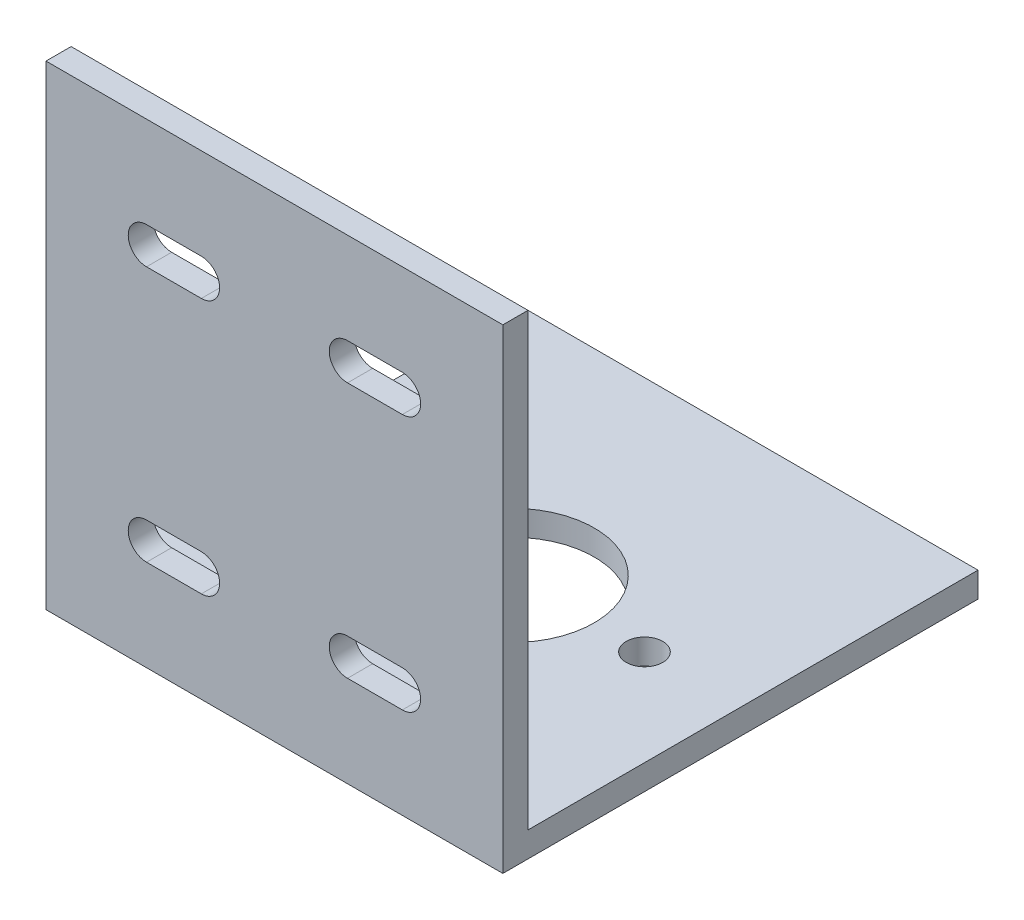
SolidWorks part; units mm, degrees
ref_plane "Front Plane" through (0, 0, 0) normal (0, 0, 1) x (1, 0, 0)
ref_plane "Top Plane" through (0, 0, 0) normal (0, 1, 0) x (1, 0, 0)
ref_plane "Right Plane" through (0, 0, 0) normal (1, 0, 0) x (0, 0, -1)
sketch "Sketch1" plane through (0, 0, 0) normal (0, 1, 0) x (1, 0, 0)
  line L1 (-25, -26) -> (25, -26)
  line L2 (-25, -26) -> (-25, 26)
  line L3 (-25, 26) -> (25, 26)
  line L4 (25, -26) -> (25, 26)
  circle A0 centre (0, 0) radius 9
  circle A1 centre (-14.5, 0) radius 2
  circle A2 centre (14.5, 0) radius 2
  point P11 (0, 0)
  dimension "D5" = 18
  dimension "D6" = 4
  dimension "D8" = 4
  dimension "D1" = 52
  dimension "D2" = 26
  dimension "D3" = 50
  dimension "D4" = 25
  dimension "D7" = 14.5
  dimension "D9" = 14.5
extrude "Boss-Extrude1" add sketch "Sketch1" along normal blind 2.75
sketch "Sketch2" plane through (0, 0, 0) normal (0, 1, 0) x (1, 0, 0)
  line L0 (25, -26) -> (25, 26) construction
  line L1 (-25, -26) -> (25, -26)
  line L2 (-25, -26) -> (-25, -23.25)
  line L3 (-25, -23.25) -> (25, -23.25)
  line L4 (25, -26) -> (25, -23.25)
  dimension "D1" = 2.75
extrude "Boss-Extrude2" add sketch "Sketch2" along normal blind 52
sketch "Sketch4" plane through (0, 0, 26) normal (0, 0, 1) x (1, 0, 0)
  line L0 (-14, 12) -> (-8, 12) construction
  line L1 (-14, 14) -> (-8, 14)
  line L2 (-14, 10) -> (-8, 10)
  line L3 (8, 12) -> (14, 12) construction
  line L4 (8, 14) -> (14, 14)
  line L5 (8, 10) -> (14, 10)
  line L6 (8, 40) -> (14, 40) construction
  line L7 (8, 42) -> (14, 42)
  line L8 (8, 38) -> (14, 38)
  line L9 (-14, 40) -> (-8, 40) construction
  line L10 (-14, 42) -> (-8, 42)
  line L11 (-14, 38) -> (-8, 38)
  line L12 (-14, 12) -> (8, 12) construction
  arc A0 (-14, 14) -> (-14, 10) centre (-14, 12) ccw
  arc A1 (-8, 10) -> (-8, 14) centre (-8, 12) ccw
  arc A2 (8, 14) -> (8, 10) centre (8, 12) ccw
  arc A3 (14, 10) -> (14, 14) centre (14, 12) ccw
  arc A4 (8, 42) -> (8, 38) centre (8, 40) ccw
  arc A5 (14, 38) -> (14, 42) centre (14, 40) ccw
  arc A6 (-14, 42) -> (-14, 38) centre (-14, 40) ccw
  arc A7 (-8, 38) -> (-8, 42) centre (-8, 40) ccw
  point P2 (-11, 12)
  point P12 (11, 12)
  point P19 (11, 40)
  point P26 (-11, 40)
  dimension "D1" = 11
  dimension "D2" = 12
  dimension "D5" = 22
  dimension "D3" = 2
  dimension "D4" = 2
extrude "Cut-Extrude1" cut sketch "Sketch4" against normal through all
equation "\"D2@Sketch1\"=\"D1@Sketch1\"/2"
equation "\"D4@Sketch1\"=\"D3@Sketch1\"/2"
equation "\"D8@Sketch1\"=\"D6@Sketch1\""
equation "\"D9@Sketch1\"=\"D7@Sketch1\""
